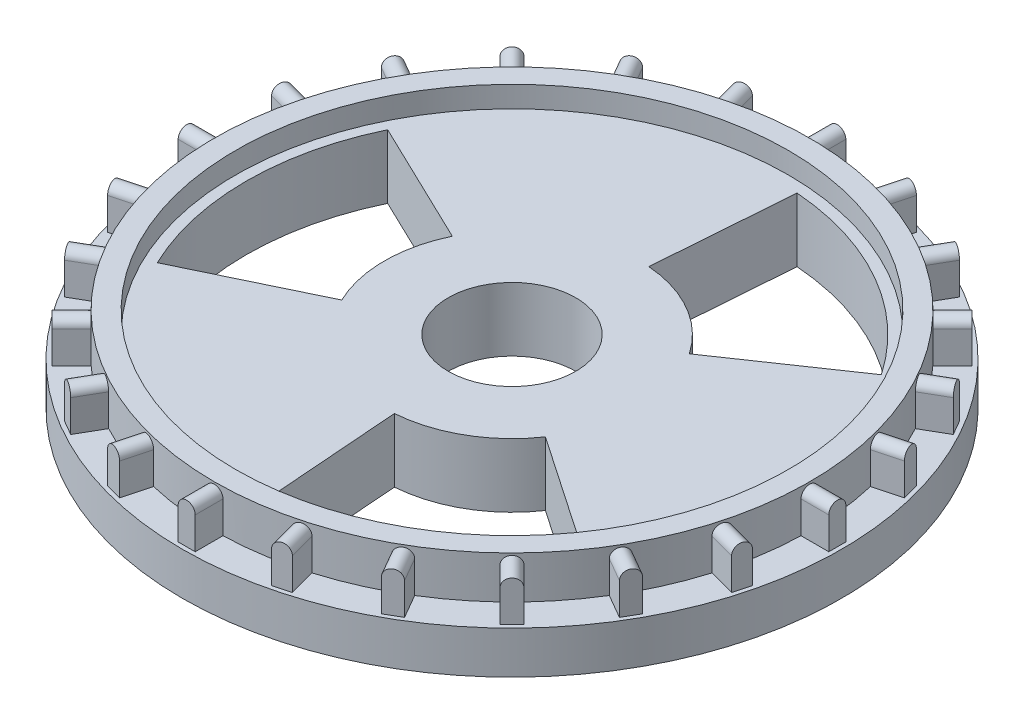
SolidWorks part; units mm, degrees
material "Alloy Steel"
ref_plane "Front Plane" through (0, 0, 0) normal (0, 0, 1) x (1, 0, 0)
ref_plane "Top Plane" through (0, 0, 0) normal (0, 1, 0) x (1, 0, 0)
ref_plane "Right Plane" through (0, 0, 0) normal (1, 0, 0) x (0, 0, -1)
sketch "Sketch1" plane through (0, 0, 0) normal (0, 1, 0) x (1, 0, 0)
  circle A0 centre (0, 0) radius 196.85
  dimension "D1" = 393.7
extrude "Boss-Extrude1" add sketch "Sketch1" along normal blind 25.4
sketch "Sketch2" plane through (0, 25.4, 0) normal (0, 1, 0) x (1, 0, 0)
  circle A0 centre (0, 0) radius 177.8
  dimension "D1" = 355.6
extrude "Boss-Extrude2" add sketch "Sketch2" along normal blind 25.4
sketch "Sketch3" plane through (0, 50.8, 0) normal (0, 1, 0) x (1, 0, 0)
  circle A0 centre (0, 0) radius 165.1
  dimension "D1" = 330.2
extrude "Cut-Extrude1" cut sketch "Sketch3" against normal blind 12.7 contours A0
ref_plane "Plane1" through (194.31, 0, 0) normal (1, 0, 0) x (0, 0, -1)
sketch "Sketch6" plane through (194.31, 0, 0) normal (1, 0, 0) x (0, 0, -1)
  line L0 (-5.08, 44.45) -> (-5.08, 25.4)
  line L1 (5.08, 44.45) -> (5.08, 25.4)
  line L2 (177.8, 25.4) -> (-177.8, 25.4) construction
  line L5 (-5.08, 25.4) -> (5.08, 25.4)
  line L7 (165.1, 50.8) -> (-165.1, 50.8) construction
  arc A0 (-5.08, 44.45) -> (5.08, 44.45) centre (0, 44.45) cw
  point P3 (10.16, 37.5339)
  point P6 (0, 49.53)
  dimension "D1" = 5.08
  dimension "D2" = 1.27
extrude "Boss-Extrude5" add sketch "Sketch6" against normal up to surface (16.5826 mm away)
pattern_circular "CirPattern2" count 24 over 360 about axis through (0, 0, 0) along (0, 1, 0) of "Boss-Extrude5"
sketch "Sketch7" plane through (0, 38.1, 0) normal (0, 1, 0) x (1, 0, 0)
  circle A0 centre (0, 0) radius 38.1
  dimension "D1" = 76.2
extrude "Cut-Extrude2" cut sketch "Sketch7" against normal through all
sketch "Sketch8" plane through (0, 38.1, 0) normal (0, 1, 0) x (1, 0, 0)
  line L0 (-68.674, 33.02) -> (-143.0709, 68.7917)
  line L1 (-68.674, -33.02) -> (-143.0709, -68.7917)
  arc A0 (-68.674, 33.02) -> (-68.674, -33.02) centre (0, 0) ccw
  arc A1 (-143.0709, 68.7917) -> (-143.0709, -68.7917) centre (0, 0) ccw
  point P1 (-142.4879, 67.5921)
  point P3 (-76.2, 0)
  point P8 (-142.5553, 67.7296)
  dimension "D1" = 152.4
  dimension "D2" = 317.5
  dimension "D3" = 66.04
extrude "Cut-Extrude3" cut sketch "Sketch8" against normal through all
pattern_circular "CirPattern3" count 3 over 360 about axis through (0, 0, 0) along (0, 1, 0) of "Cut-Extrude3"
